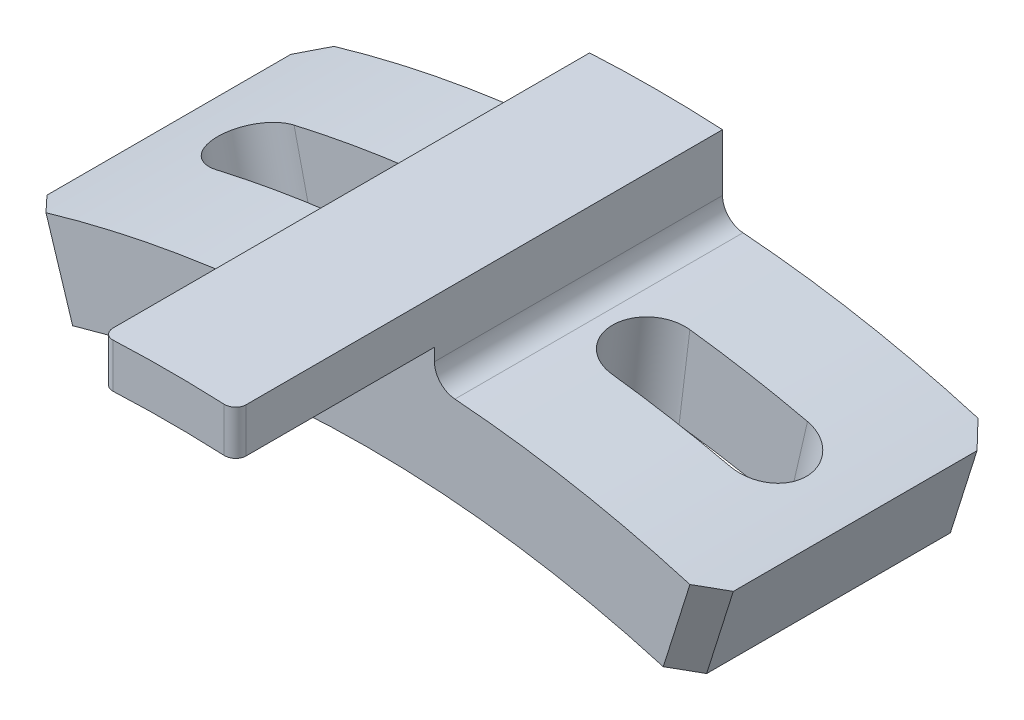
SolidWorks part; units mm, degrees
material "PETG"
ref_plane "Спереди" through (0, 0, 0) normal (0, 0, 1) x (1, 0, 0)
ref_plane "Сверху" through (0, 0, 0) normal (0, 1, 0) x (1, 0, 0)
ref_plane "Справа" through (0, 0, 0) normal (1, 0, 0) x (0, 0, -1)
sketch "Эскиз1" plane through (0, 0, 0) normal (0, 0, 1) x (1, 0, 0)
  line L0 (14.2835, 45.3016) -> (15.4863, 49.1164)
  line L1 (-14.2835, 45.3016) -> (-15.4863, 49.1164)
  line L2 (0, 0) -> (0, 84.5239) construction
  line L3 (-3, 54.9181) -> (-3, 51.4125)
  line L4 (3, 54.9181) -> (3, 51.4125)
  arc A0 (14.2835, 45.3016) -> (-14.2835, 45.3016) centre (0, 0) ccw
  arc A1 (3, 54.9181) -> (-3, 54.9181) centre (0, 0) ccw
  arc A2 (15.4863, 49.1164) -> (3, 51.4125) centre (0, 0) ccw
  circle A3 centre (0, 0) radius 55 construction
  circle A4 centre (0, 0) radius 47.5 construction
  arc A5 (-3, 51.4125) -> (-15.4863, 49.1164) centre (0, 0) ccw
  arc A7 (15.4863, 49.1164) -> (-15.4863, 49.1164) centre (0, 0) ccw construction
  point P6 (59.769, 18.2732)
  point P7 (70, 0)
  dimension "D1" = 95
  dimension "D4" = 4
  dimension "D3" = 17.5
  dimension "D5" = 6
  dimension "D2" = 7.5
extrude "Бобышка-Вытянуть1" add sketch "Эскиз1" along normal mid plane 13
sketch "Эскиз2" plane through (0, 0, 6.5) normal (0, 0, 1) x (1, 0, 0)
  line L0 (3, 51.4125) -> (3, 54.9181) construction
  line L1 (-3, 54.9181) -> (-3, 51.4125) construction
  line L2 (3, 52.915) -> (3, 54.9181)
  line L3 (-3, 54.9181) -> (-3, 52.915)
  arc A0 (3, 54.9181) -> (-3, 54.9181) centre (0, 0) ccw construction
  arc A1 (3, 54.9181) -> (-3, 54.9181) centre (0, 0) ccw
  arc A2 (2.8909, 52.9211) -> (-2.8909, 52.9211) centre (0, 0) ccw construction
  arc A6 (3, 52.915) -> (-3, 52.915) centre (0, 0) ccw
  dimension "D1" = 2
extrude "Бобышка-Вытянуть2" add sketch "Эскиз2" along normal blind 9
sketch "Эскиз4" plane through (0, 0, 0) normal (0, 0, 1) x (1, 0, 0)
  line L0 (0, 0) -> (11.585, 50.1801) construction
  line L1 (15.2022, 58.0685) -> (10.7032, 38.5811)
  line L4 (10.7032, 38.5811) -> (8.998, 38.9748)
  line L5 (15.2022, 58.0685) -> (13.4971, 58.4622)
  line L6 (8.998, 38.9748) -> (13.4971, 58.4622)
  line L7 (0, 0) -> (0, 47.5) construction
  arc A0 (15.4863, 49.1164) -> (3, 51.4125) centre (0, 0) ccw construction
  arc A1 (14.2835, 45.3016) -> (-14.2835, 45.3016) centre (0, 0) ccw construction
  dimension "D1" = 3.5
  dimension "D2" = 13
  dimension "D3" = 40
  dimension "D4" = 20
  dimension "D5" = 2.2906
revolve "Вырез-Повернуть1" cut sketch "Эскиз4" angle 360 about L0
pattern_circular "Круговой массив1" count 2 every 6 about axis through (0, 0, 6.5) along (0, 0, -1) of "Вырез-Повернуть1"
sketch "Эскиз6" plane through (0, 0, 0) normal (0, 0, 1) x (1, 0, 0)
  line L0 (5.7888, 47.1459) -> (6.2763, 51.1161)
  line L1 (10.6852, 46.2826) -> (11.585, 50.1801)
  arc A0 (14.2835, 45.3016) -> (-14.2835, 45.3016) centre (0, 0) ccw construction
  arc A1 (15.4863, 49.1164) -> (3, 51.4125) centre (0, 0) ccw construction
  arc A2 (10.6852, 46.2826) -> (5.7888, 47.1459) centre (0, 0) ccw
  arc A3 (11.585, 50.1801) -> (6.2763, 51.1161) centre (0, 0) ccw
  arc A8 (7.5218, 46.9007) -> (4.0479, 47.3272) centre (0, 0) ccw construction
  arc A10 (8.0096, 50.8733) -> (4.5357, 51.2999) centre (0, 0) ccw construction
  arc A11 (12.3831, 45.8575) -> (8.9728, 46.6448) centre (0, 0) ccw construction
  arc A12 (13.2834, 49.7574) -> (9.8731, 50.5447) centre (0, 0) ccw construction
extrude "Вырез-Вытянуть2" cut sketch "Эскиз6" against normal mid plane 3.5
mirror "Зеркальное отражение1" about plane through (0, 0, 0) normal (1, 0, 0) of "Вырез-Вытянуть2", "Круговой массив1", "Вырез-Повернуть1"
fillet "Скругление1" radius 1 2 edges at (-3, 51.4125, 0) (3, 51.4125, 0)
chamfer "Фаска1" distance 1 angle 45 4 edges at (14.8849, 47.209, 6.5) (-14.8849, 47.209, 6.5) (-14.8849, 47.209, -6.5) (14.8849, 47.209, -6.5)
fillet "Скругление2" radius 0.5 2 edges at (3, 53.9166, 15.5) (-3, 53.9166, 15.5)
